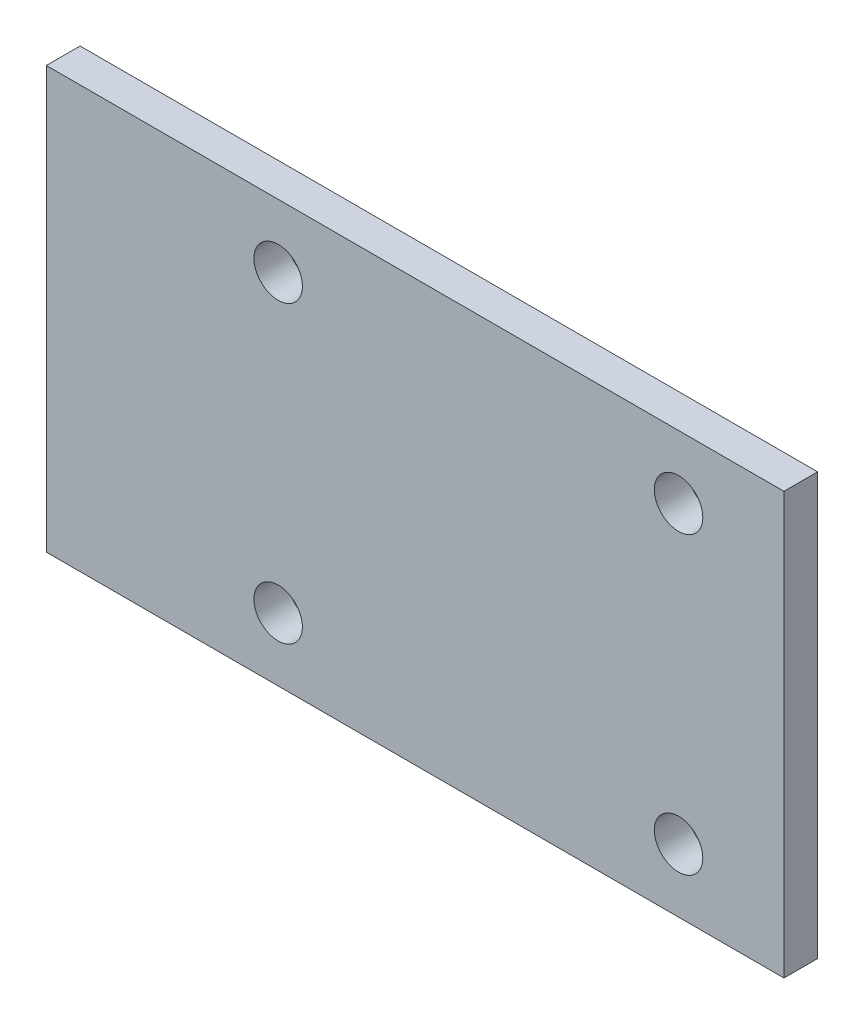
SolidWorks part; units mm, degrees
material "A-Glass Fiber"
ref_plane "Front Plane" through (0, 0, 0) normal (0, 0, 1) x (1, 0, 0)
ref_plane "Top Plane" through (0, 0, 0) normal (0, 1, 0) x (1, 0, 0)
ref_plane "Right Plane" through (0, 0, 0) normal (1, 0, 0) x (0, 0, -1)
sketch "Sketch1" plane through (0, 0, 0) normal (0, 0, 1) x (1, 0, 0)
  line L1 (-17.5, 10) -> (17.5, 10)
  line L2 (-17.5, 10) -> (-17.5, -10)
  line L3 (-17.5, -10) -> (17.5, -10)
  line L4 (17.5, 10) -> (17.5, -10)
  line L5 (-17.5, 10) -> (17.5, -10) construction
  line L6 (-17.5, -10) -> (17.5, 10) construction
  point P0 (0, 0)
  dimension "D1" = 20
  dimension "D2" = 35
extrude "PCB" add sketch "Sketch1" along normal blind 1.6
sketch "Sketch2" plane through (0, 0, 0) normal (0, 0, 1) x (1, 0, 0)
  line L0 (-17.5, 7) -> (17.5, 7) construction
  line L1 (-17.5, 10) -> (-17.5, -10) construction
  line L2 (17.5, -10) -> (17.5, 10) construction
  line L3 (-17.5, -7) -> (17.5, -7) construction
  line L4 (17.5, 10) -> (-17.5, 10) construction
  line L5 (0, 0) -> (17.5, 0) construction
  line L6 (12.5, 7) -> (12.5, -7) construction
  line L7 (-6.5, 7) -> (-6.5, -7) construction
  circle A0 centre (12.5, 7) radius 1.15
  circle A1 centre (-6.5, 7) radius 1.15
  circle A2 centre (-6.5, -7) radius 1.15
  circle A3 centre (12.5, -7) radius 1.15
  dimension "D2" = 2.3
  dimension "D1" = 3
  dimension "D3" = 5
  dimension "D4" = 11
extrude "Holes" cut sketch "Sketch2" along normal up to next
